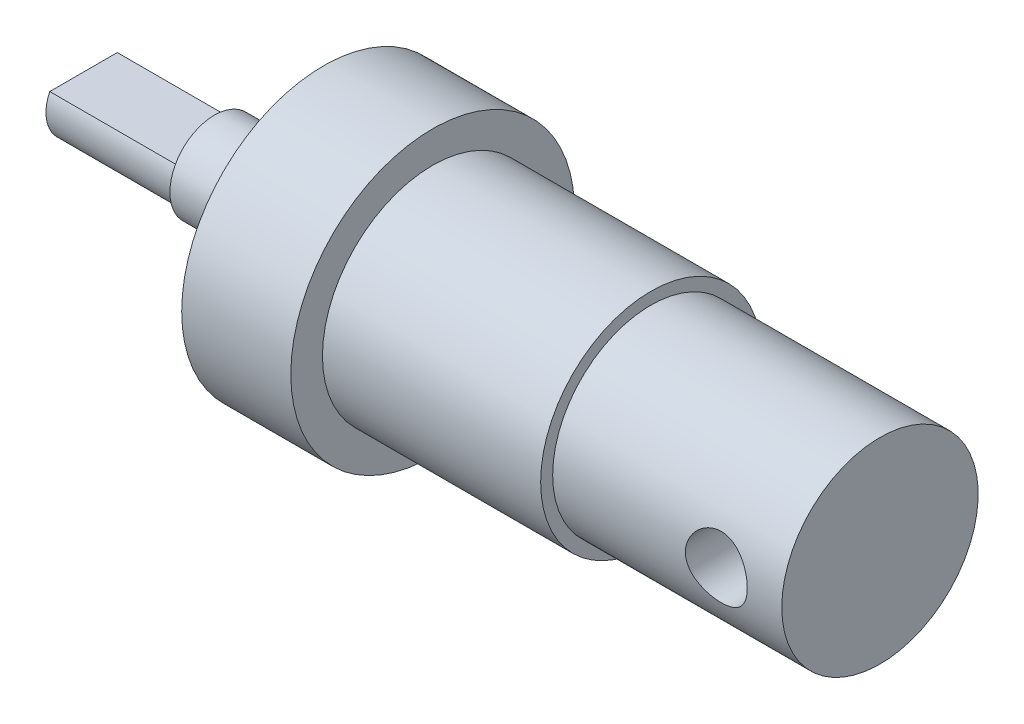
SolidWorks part; units mm, degrees
ref_plane "前视基准面" through (0, 0, 0) normal (0, 0, 1) x (1, 0, 0)
ref_plane "上视基准面" through (0, 0, 0) normal (0, 1, 0) x (1, 0, 0)
ref_plane "右视基准面" through (0, 0, 0) normal (1, 0, 0) x (0, 0, -1)
sketch "草图1" plane through (0, 0, 0) normal (0, 0, 1) x (1, 0, 0)
  line L0 (0, 0) -> (20.5, 0)
  line L1 (20.5, 0) -> (20.5, 4.5)
  line L2 (10, 5.05) -> (0, 5.05)
  line L3 (0, 5.05) -> (0, 6.5)
  line L4 (0, 6.5) -> (-5, 6.5)
  line L5 (-5, 6.5) -> (-5, 5)
  line L8 (-5, 0) -> (0, 0)
  line L9 (0, 5.05) -> (10, 5.05)
  line L10 (10, 5.05) -> (10, 4.5)
  line L11 (10, 4.5) -> (20.5, 4.5)
  line L12 (-5, 5) -> (-5, 0)
  dimension "D1" = 6.5
  dimension "D2" = 5
  dimension "D3" = 4.5
  dimension "D4" = 10
  dimension "D5" = 10.5
  dimension "D6" = 5.05
revolve "旋转1" add sketch "草图1" angle 360 about L8
ref_plane "基准面4" through (17.5, 0, 0) normal (1, 0, 0) x (0, 0, -1)
sketch "草图3" plane through (17.5, 0, 0) normal (1, 0, 0) x (0, 0, -1)
  line L0 (-6.6805, 0) -> (7.6, -0.0675) construction
  line L1 (-6.6805, 0) -> (-6.6805, 1.4075)
  line L2 (-6.6805, 1.4075) -> (7.6, 1.4075)
  line L3 (7.6, 1.4075) -> (7.6, -0.0675)
  line L4 (-6.6805, 0) -> (7.6, -0.0675)
revolve "切除-旋转1" cut sketch "草图3" angle 360 about L0
sketch "草图4" plane through (-5, 0, 0) normal (-1, 0, 0) x (0, 0, 1)
  line L3 (0, 0.75) -> (1.5479, 0.75)
  line L4 (0.0465, 0.75) -> (-1.5479, 0.75)
  arc A2 (-1.5479, 0.75) -> (1.5479, 0.75) centre (0, 0) ccw
extrude "凸台-拉伸2" add sketch "草图4" along normal blind 11
sketch "草图5" plane through (-5, 0, 0) normal (-1, 0, 0) x (0, 0, 1)
  circle A0 centre (0, 0) radius 2.04
extrude "凸台-拉伸3" add sketch "草图5" along normal blind 5
